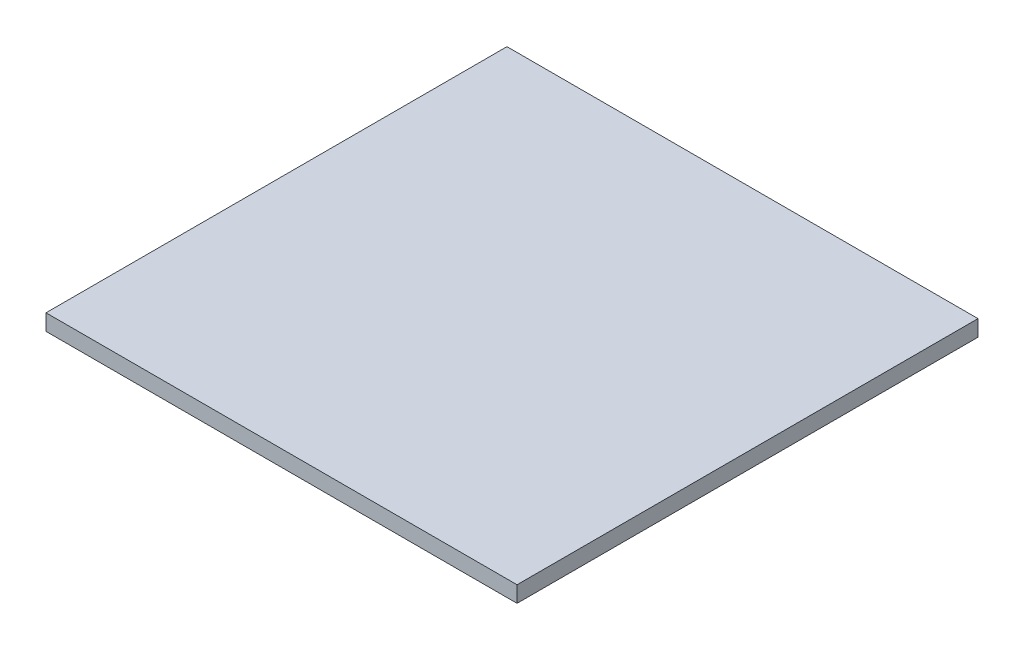
SolidWorks part; units mm, degrees
ref_plane "Front Plane" through (0, 0, 0) normal (0, 0, 1) x (1, 0, 0)
ref_plane "Top Plane" through (0, 0, 0) normal (0, 1, 0) x (1, 0, 0)
ref_plane "Right Plane" through (0, 0, 0) normal (1, 0, 0) x (0, 0, -1)
sketch "Sketch1" plane through (0, -12.6, 0) normal (0, -1, 0) x (1, 0, 0)
  line L1 (-73.0346, -71.47) -> (73.0346, -71.47)
  line L2 (-73.0346, -71.47) -> (-73.0346, 71.47)
  line L3 (-73.0346, 71.47) -> (73.0346, 71.47)
  line L4 (73.0346, -71.47) -> (73.0346, 71.47)
  line L5 (-73.0346, -71.47) -> (73.0346, 71.47) construction
  line L6 (-73.0346, 71.47) -> (73.0346, -71.47) construction
  point P0 (0, 0)
extrude "Boss-Extrude1" add sketch "Sketch1" along normal blind 5
